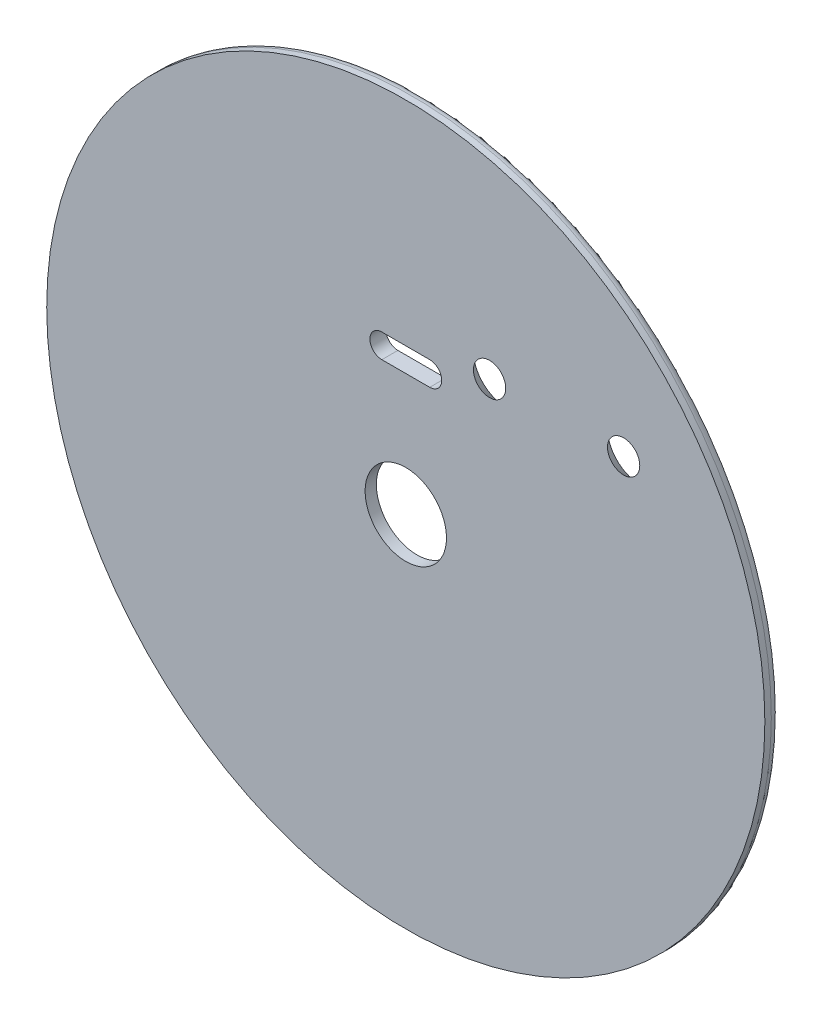
SolidWorks part; units mm, degrees
material "AISI 1020"
ref_plane "Plano frontal" through (0, 0, 0) normal (0, 0, 1) x (1, 0, 0)
ref_plane "Plano superior" through (0, 0, 0) normal (0, 1, 0) x (1, 0, 0)
ref_plane "Plano direito" through (0, 0, 0) normal (1, 0, 0) x (0, 0, -1)
sketch "Esboço1" plane through (0, 0, 0) normal (0, 0, 1) x (1, 0, 0)
  circle A0 centre (0, 0) radius 75
  circle A1 centre (0, 0) radius 8.5
  dimension "D1" = 17
  dimension "D2" = 150
extrude "Extrusão1" add sketch "Esboço1" along normal blind 3.35
sketch "Esboço2" plane through (0, 0, 0) normal (0, 0, -1) x (-1, 0, 0)
  circle A0 centre (0, 0) radius 24.25
  dimension "D1" = 48.5
extrude "Corte-extrusão1" cut sketch "Esboço2" against normal blind 1
sketch "Esboço6" plane through (0, 0, 0) normal (0, 0, -1) x (-1, 0, 0)
  line L0 (-5, 28) -> (5, 28) construction
  line L1 (0, 0) -> (0, 28) construction
  line L2 (-5, 25.5) -> (5, 25.5)
  line L3 (-5, 30.5) -> (5, 30.5)
  arc A0 (-5, 25.5) -> (-5, 30.5) centre (-5, 28) cw
  arc A1 (5, 25.5) -> (5, 30.5) centre (5, 28) ccw
  dimension "D3" = 10
  dimension "D4" = 28
  dimension "D1" = 2.5
  dimension "D2" = 2.5
extrude "Corte-extrusão3" cut sketch "Esboço6" against normal blind 10
hole_wizard "Escareado para SFHCS M62" [suppressed] positions "3DSketch2" profile "Esboço7" countersink size "M6" standard "Métrico Ansi"
sketch3d "3DSketch2"
  line L0 (-7.5, 28, 0) -> (-17.5, 28, 0) construction
  line L1 (-17.5, 28, 0) -> (-17.5, 33.25, 0) construction
  arc A2 (-5, 25.5, 0) -> (-5, 30.5, 0) centre (-5, 28, 0) ccw construction
  point P0 (-17.5, 33.25, 0)
  point P15 (-5, 28, -2.5)
  dimension "D1" = 5.25
  dimension "D2" = 10
sketch "Esboço7" plane through (-17.5, 33.25, 0) normal (1, 0, 0) x (0, 1, 0)
  line L0 (0, 0) -> (0, 3.35)
  line L1 (0, 3.35) -> (3.3, 3.35)
  line L2 (3.3, 3.35) -> (3.3, 3.42)
  line L3 (3.3, 3.42) -> (6.72, 0)
  line L5 (6.72, 0) -> (0, 0)
  line L6 (-3.3, 3.42) -> (-6.72, 0) construction
  line L11 (0, -6.35) -> (0, 107.95) construction
  dimension "Thru Hole Dia." = 6.6
  dimension "Thru Hole Depth" = 3.35
  dimension "Near C'Sink Dia." = 13.44
  dimension "Near C'Sink Angle" = 90
pattern_linear "LPattern2" [suppressed] count 2 spacing 28
hole_wizard "Escareado para SFHCS M63" positions "3DSketch3" profile "Esboço8" countersink size "M6" standard "Métrico Ansi" end condition through all
sketch3d "3DSketch3"
  line L1 (7.5, 28, 0) -> (17.5, 28, 0) construction
  line L2 (17.5, 28, 0) -> (17.5, 33.25, 0) construction
  arc A0 (5, 30.5, 0) -> (5, 25.5, 0) centre (5, 28, 0) ccw construction
  point P0 (17.5, 33.25, 0)
  point P12 (5, 28, -2.5)
  dimension "D1" = 5.25
  dimension "D2" = 10
sketch "Esboço8" plane through (17.5, 33.25, 0) normal (1, 0, 0) x (0, 1, 0)
  line L0 (0, 0) -> (0, 3.35)
  line L1 (0, 3.35) -> (3.3, 3.35)
  line L2 (3.3, 3.35) -> (3.3, 3.42)
  line L3 (3.3, 3.42) -> (6.72, 0)
  line L5 (6.72, 0) -> (0, 0)
  line L6 (-3.3, 3.42) -> (-6.72, 0) construction
  line L11 (0, -6.35) -> (0, 107.95) construction
  dimension "Thru Hole Dia." = 6.6
  dimension "Thru Hole Depth" = 3.35
  dimension "Near C'Sink Dia." = 13.44
  dimension "Near C'Sink Angle" = 90
pattern_linear "LPattern3" count 2 spacing 28 along (1, 0, 0) of "Escareado para SFHCS M63"
fillet "Filete1" radius 2 1 edges at (75, 0, 0)
